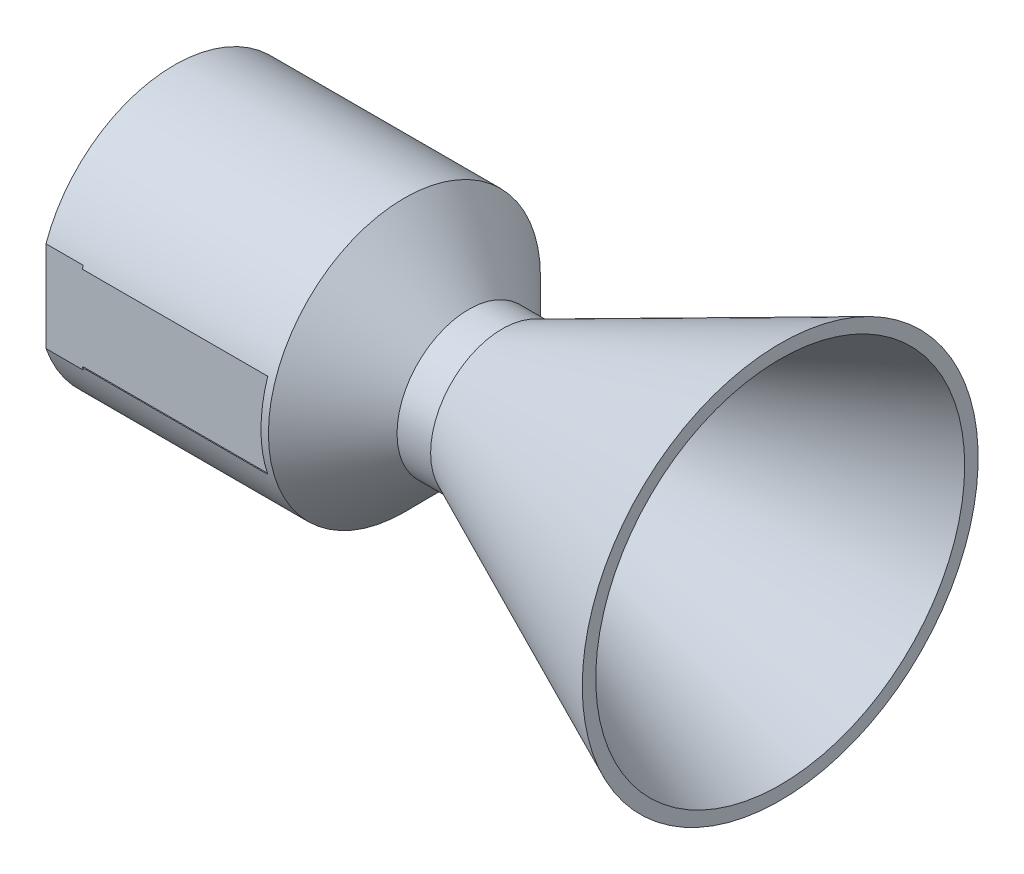
SolidWorks part; units mm, degrees
other "Markup1"
sketch "Sketch2" plane through (-326.7403, -235.8036, 235.8036) normal (0, 0, 1) x (1, 0, 0)
other "Markup2"
sketch "Sketch3" plane through (-326.7403, -235.8036, 235.8036) normal (0, 0, 1) x (1, 0, 0)
other "Markup3"
sketch "Sketch4" plane through (-326.7403, -235.8036, 235.8036) normal (0, 0, 1) x (1, 0, 0)
ref_plane "Front Plane" through (0, 0, 0) normal (0, 0, 1) x (1, 0, 0)
ref_plane "Top Plane" through (0, 0, 0) normal (0, 1, 0) x (1, 0, 0)
ref_plane "Right Plane" through (0, 0, 0) normal (1, 0, 0) x (0, 0, -1)
sketch "Sketch1" plane through (0, 0, 0) normal (0, 0, 1) x (1, 0, 0)
  line L0 (0, 0) -> (89.9154, 0) construction
  line L1 (0, 20.2545) -> (28.7226, 20.2545)
  line L2 (28.7226, 20.2545) -> (38.2981, 10.6789)
  line L3 (38.2981, 10.6789) -> (43.3027, 10.6789)
  line L4 (43.3027, 10.6789) -> (84.6786, 29.4755)
  line L5 (0, 17.6579) -> (0, 0)
  line L6 (84.6786, 27.4684) -> (84.6786, 0)
  line L7 (0, 0) -> (84.6786, 0)
  line L8 (0, 17.6579) -> (28.7226, 17.6579)
  line L9 (28.7226, 17.6579) -> (37.7363, 8.6442)
  line L10 (37.7363, 8.6442) -> (43.3027, 8.6442)
  line L11 (43.3027, 8.6442) -> (84.6786, 27.4684)
  line L12 (0, 20.2545) -> (0, 17.6579)
  line L13 (84.6786, 29.4755) -> (84.6786, 27.4684)
  dimension "D1" = 84.6786
revolve "Revolve1" add sketch "Sketch1" angle 360 about L7
scale "Scale1" scale about centroid uniform scaling yes scale factor 3
sketch "Sketch5" plane through (0, 0, 0) normal (1, 0, 0) x (0, 0, -1)
  line L1 (63.8096, -18.9973) -> (57.7175, -18.9973)
  line L2 (63.8096, -18.9973) -> (63.8096, 18.9973)
  line L3 (63.8096, 18.9973) -> (57.7175, 18.9973)
  line L4 (57.7175, -18.9973) -> (57.7175, 18.9973)
  line L5 (63.8096, -18.9973) -> (57.7175, 18.9973) construction
  line L6 (63.8096, 18.9973) -> (57.7175, -18.9973) construction
  line L7 (-57.282, -18.9973) -> (-64.2451, -18.9973)
  line L8 (-57.282, -18.9973) -> (-57.282, 18.9973)
  line L9 (-57.282, 18.9973) -> (-64.2451, 18.9973)
  line L10 (-64.2451, -18.9973) -> (-64.2451, 18.9973)
  line L11 (-57.282, -18.9973) -> (-64.2451, 18.9973) construction
  line L12 (-57.282, 18.9973) -> (-64.2451, -18.9973) construction
  circle A0 centre (0, 0) radius 60.7636 construction
  point P0 (60.7636, 0)
  point P7 (-60.7636, 0)
extrude "Cut-Extrude1" cut sketch "Sketch5" against normal through all
scale "Scale2" scale about centroid uniform scaling yes scale factor 0.6
sketch "Sketch6" plane through (-32.3129, 0, 0) normal (-1, 0, 0) x (0, 0, 1)
  line L0 (-34.6856, 11.3984) -> (-34.6856, -11.3984)
  line L1 (34.3141, 11.3984) -> (34.3141, -11.3984)
  line L2 (34.3141, 11.3984) -> (34.3141, 12.1636)
  line L3 (34.3141, -11.3984) -> (34.3141, -12.1636)
  arc A1 (34.3141, 12.1636) -> (-34.6856, 11.3984) centre (-0.0551, 0) ccw
  arc A2 (-34.6856, -11.3984) -> (34.3141, -12.1636) centre (-0.0551, 0) ccw
extrude "Boss-Extrude1" add sketch "Sketch6" along normal blind 10
equation "\"m\"=0.01"
